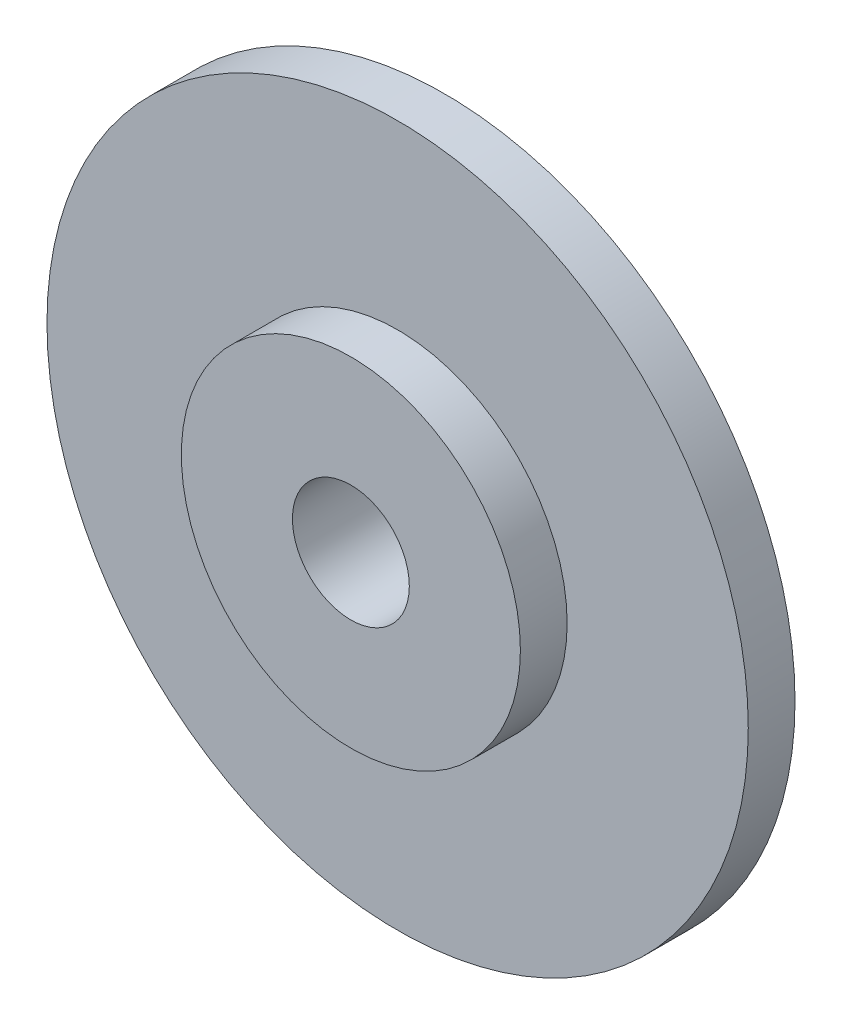
SolidWorks part; units mm, degrees
ref_plane "Front Plane" through (0, 0, 0) normal (0, 0, 1) x (1, 0, 0)
ref_plane "Top Plane" through (0, 0, 0) normal (0, 1, 0) x (1, 0, 0)
ref_plane "Right Plane" through (0, 0, 0) normal (1, 0, 0) x (0, 0, -1)
sketch "Sketch1" plane through (0, 0, 0) normal (0, 0, 1) x (1, 0, 0)
  circle A0 centre (0, 0) radius 47.625
  dimension "D1" = 95.25
extrude "Boss-Extrude1" add sketch "Sketch1" along normal blind 6.35
sketch "Sketch2" plane through (0, 0, 6.35) normal (0, 0, 1) x (1, 0, 0)
  circle A0 centre (0, 0) radius 23.0251
  dimension "D1" = 46.0502
extrude "Boss-Extrude2" add sketch "Sketch2" along normal blind 6.35
sketch "Sketch4" plane through (0, 0, 0) normal (0, 0, 1) x (1, 0, 0)
  circle A0 centre (0, 0) radius 7.9375
  dimension "D1" = 15.875
extrude "Cut-Extrude2" cut sketch "Sketch4" along normal through all
sketch "Sketch5" plane through (0, 0, 0) normal (0, 0, -1) x (-1, 0, 0)
  line L0 (0, 0) -> (0, 7.9375)
  circle A0 centre (0, 0) radius 7.9375 construction
  circle A1 centre (0, 0) radius 47.625 construction
  point P6 (0, -47.625)
